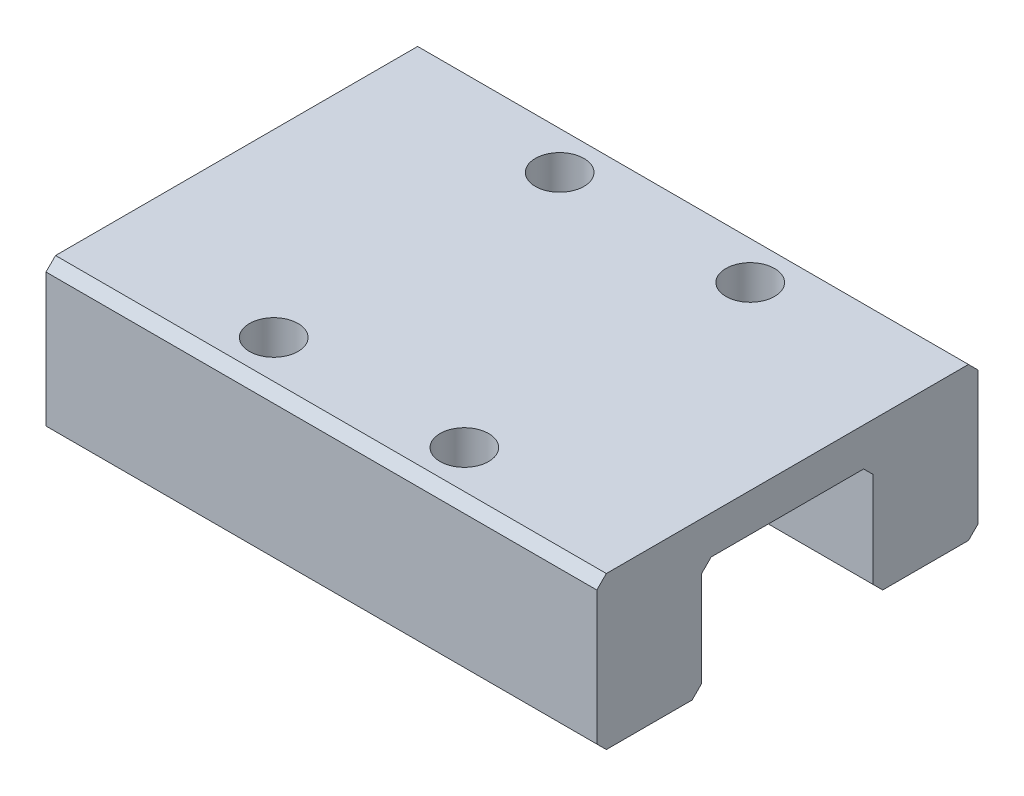
SolidWorks part; units mm, degrees
material "普通碳钢"
ref_plane "前视基准面" through (0, 0, 0) normal (0, 0, 1) x (1, 0, 0)
ref_plane "上视基准面" through (0, 0, 0) normal (0, 1, 0) x (1, 0, 0)
ref_plane "右视基准面" through (0, 0, 0) normal (1, 0, 0) x (0, 0, -1)
sketch "草图2" plane through (0, 0, 0) normal (1, 0, 0) x (0, 0, -1)
  line L0 (-4.5, 0) -> (4.5, 0)
  line L1 (4.5, 0) -> (4.5, -6)
  line L2 (4.5, -6) -> (10, -6)
  line L3 (10, -6) -> (10, 2)
  line L4 (0, 55.2379) -> (0, -46.8755) construction
  line L5 (10, 2) -> (-10, 2)
  line L6 (-10, -6) -> (-10, 2)
  line L7 (-4.5, -6) -> (-10, -6)
  line L8 (-4.5, 0) -> (-4.5, -6)
  point P10 (0, 2)
  point P11 (0, 0)
  dimension "D1" = 8
  dimension "D2" = 2
  dimension "D3" = 4.5
  dimension "D4" = 10
extrude "拉伸1" add sketch "草图2" along normal blind 28.9
chamfer "倒角1" distance 0.5 angle 45 8 edges at (14.45, 0, 4.5) (14.45, -6, -4.5) (14.45, 0, -4.5) (14.45, -6, 10) (14.45, -6, 4.5) (14.45, -6, -10) (14.45, 2, -10) (14.45, 2, 10)
sketch "草图3" plane through (0, 2, 0) normal (0, 1, 0) x (1, 0, 0)
  line L0 (14.45, 23.1296) -> (14.45, -26.0824) construction
  line L1 (28.9, 9.5) -> (28.9, -9.5) construction
  line L2 (-5.6521, 0) -> (44.7927, 0) construction
  circle A0 centre (9.45, 7.5) radius 1.275
  circle A1 centre (19.45, 7.5) radius 1.275
  circle A2 centre (19.45, -7.5) radius 1.275
  circle A3 centre (9.45, -7.5) radius 1.275
  dimension "D2" = 5
  dimension "D3" = 7.5
  dimension "D4" = 2.55
  dimension "D1" = 14.45
extrude "拉伸2" cut sketch "草图3" against normal blind 3
cosmetic thread "装饰螺纹线9" parameters "D2"=3
cosmetic thread "装饰螺纹线10" parameters "D2"=3
cosmetic thread "装饰螺纹线11" parameters "D2"=3
cosmetic thread "装饰螺纹线12" parameters "D2"=3
